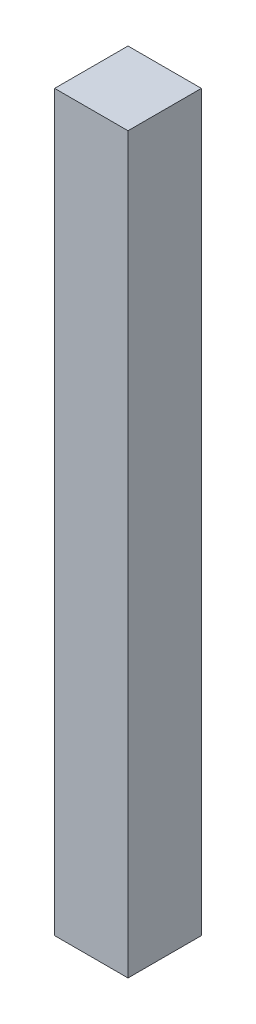
SolidWorks part; units mm, degrees
ref_plane "Plan de face" through (0, 0, 0) normal (0, 0, 1) x (1, 0, 0)
ref_plane "Plan de dessus" through (0, 0, 0) normal (0, 1, 0) x (1, 0, 0)
ref_plane "Plan de droite" through (0, 0, 0) normal (1, 0, 0) x (0, 0, -1)
sketch "Esquisse1" plane through (0, 0, 0) normal (0, 0, 1) x (1, 0, 0)
  line L1 (0, 0) -> (-5, 0)
  line L2 (0, 0) -> (0, -50)
  line L3 (0, -50) -> (-5, -50)
  line L4 (-5, 0) -> (-5, -50)
  dimension "D1" = 5
  dimension "D2" = 50
extrude "Boss.-Extru.1" add sketch "Esquisse1" along normal blind 5
